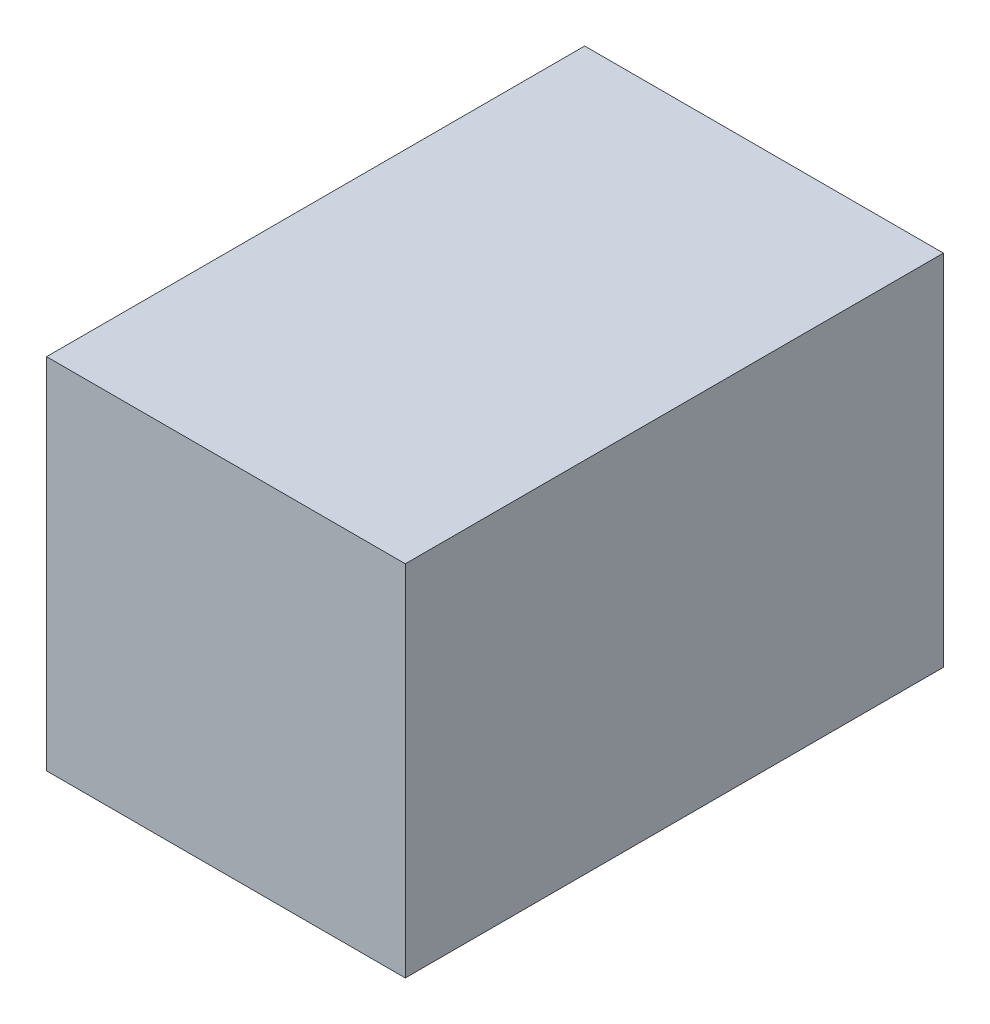
SolidWorks part; units mm, degrees
material "1023 Carbon Steel Sheet (SS)"
ref_plane "Front Plane" through (0, 0, 0) normal (0, 0, 1) x (1, 0, 0)
ref_plane "Top Plane" through (0, 0, 0) normal (0, 1, 0) x (1, 0, 0)
ref_plane "Right Plane" through (0, 0, 0) normal (1, 0, 0) x (0, 0, -1)
sketch "Sketch1" plane through (0, 0, 20.1102) normal (0, 0, 1) x (1, 0, 0)
  line L2 (-1.5875, 3.5052) -> (1.5875, 3.5052)
  line L3 (-1.5875, 3.5052) -> (-1.5875, 6.6802)
  line L4 (-1.5875, 6.6802) -> (1.5875, 6.6802)
  line L5 (1.5875, 3.5052) -> (1.5875, 6.6802)
  line L6 (-1.5875, 3.5052) -> (1.5875, 6.6802) construction
  line L7 (-1.5875, 6.6802) -> (1.5875, 3.5052) construction
  point P2 (0, 5.0927)
  dimension "D1" = 3.175
extrude "Boss-Extrude1" add sketch "Sketch1" along normal blind 4.7625 from offset 1.5875
